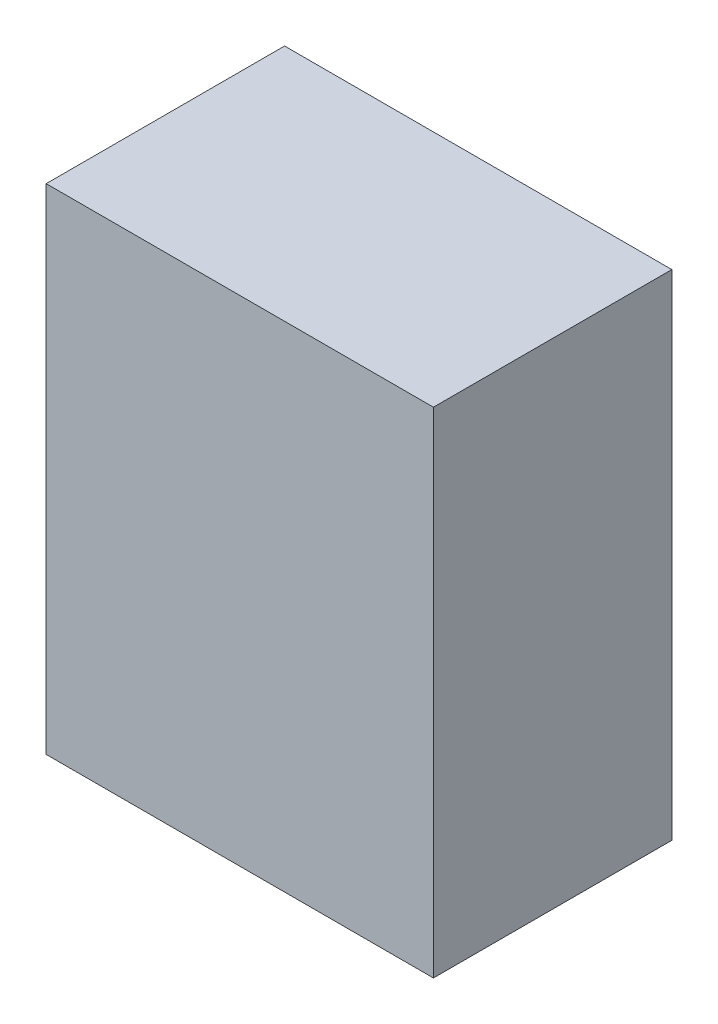
SolidWorks part; units mm, degrees
ref_plane "Front Plane" through (0, 0, 0) normal (0, 0, 1) x (1, 0, 0)
ref_plane "Top Plane" through (0, 0, 0) normal (0, 1, 0) x (1, 0, 0)
ref_plane "Right Plane" through (0, 0, 0) normal (1, 0, 0) x (0, 0, -1)
sketch "Sketch1" plane through (0, 0, 0) normal (0, 0, 1) x (1, 0, 0)
  line L0 (0, 0) -> (129.9422, 0)
  line L1 (129.9422, 0) -> (129.9422, -165.8828)
  line L2 (129.9422, -165.8828) -> (0, -165.8828)
  line L3 (0, -165.8828) -> (0, 0)
extrude "Boss-Extrude1" add sketch "Sketch1" along normal blind 80
